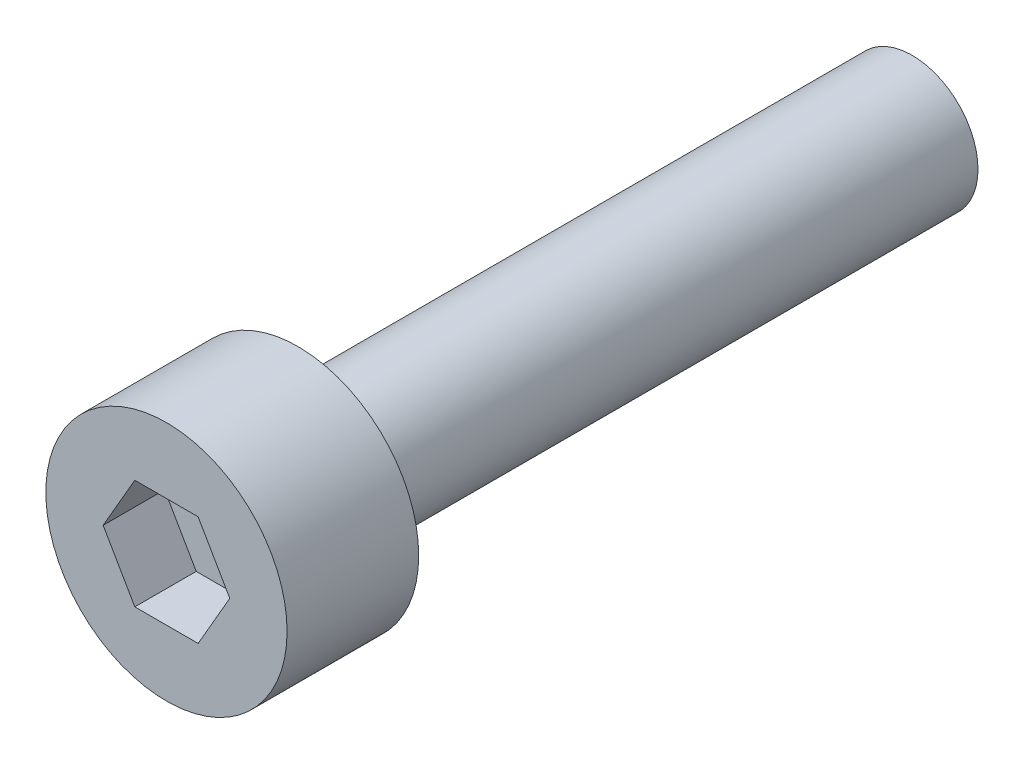
SolidWorks part; units mm, degrees
ref_plane "前视基准面" through (0, 0, 0) normal (0, 0, 1) x (1, 0, 0)
ref_plane "上视基准面" through (0, 0, 0) normal (0, 1, 0) x (1, 0, 0)
ref_plane "右视基准面" through (0, 0, 0) normal (1, 0, 0) x (0, 0, -1)
other "Configuration Table"
sketch "ISO4762_head_D5p5_h3_Sketch" plane through (0, 0, 0) normal (0, 0, 1) x (1, 0, 0)
  circle A0 centre (0, 0) radius 2.75
extrude "ISO4762_head_D5p5_h3" add sketch "ISO4762_head_D5p5_h3_Sketch" along normal blind 3 separate body
sketch "M3_major_diameter_envelope_Sketch" plane through (0, 0, 0) normal (0, 0, 1) x (1, 0, 0)
  circle A0 centre (0, 0) radius 1.5
extrude "M3_major_diameter_envelope" add sketch "M3_major_diameter_envelope_Sketch" along normal blind 14 from offset 14
sketch "Hex_socket_2p5AF_Sketch" plane through (0, 0, 0) normal (0, 0, 1) x (1, 0, 0)
  line L0 (1.4434, 0) -> (0.7217, 1.25)
  line L1 (0.7217, 1.25) -> (-0.7217, 1.25)
  line L2 (-0.7217, 1.25) -> (-1.4434, 0)
  line L3 (-1.4434, 0) -> (-0.7217, -1.25)
  line L4 (-0.7217, -1.25) -> (0.7217, -1.25)
  line L5 (0.7217, -1.25) -> (1.4434, 0)
extrude "Hex_socket_2p5AF" cut sketch "Hex_socket_2p5AF_Sketch" along normal blind 1.4 from offset 1.6
